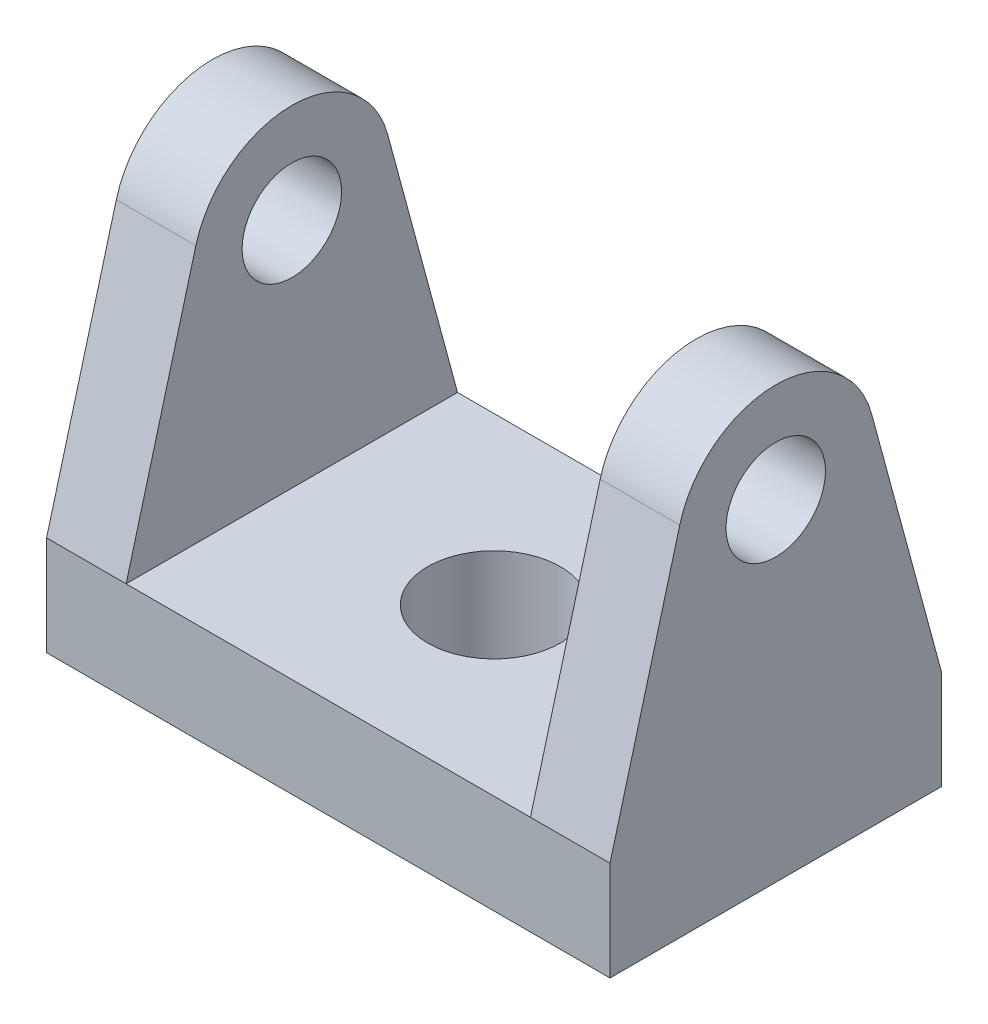
SolidWorks part; units mm, degrees
ref_plane "Front Plane" through (0, 0, 0) normal (0, 0, 1) x (1, 0, 0)
ref_plane "Top Plane" through (0, 0, 0) normal (0, 1, 0) x (1, 0, 0)
ref_plane "Right Plane" through (0, 0, 0) normal (1, 0, 0) x (0, 0, -1)
sketch "Sketch1" plane through (0, 0, 0) normal (0, 1, 0) x (1, 0, 0)
  line L1 (42.5, 25) -> (-42.5, 25)
  line L2 (42.5, 25) -> (42.5, -25)
  line L3 (42.5, -25) -> (-42.5, -25)
  line L4 (-42.5, 25) -> (-42.5, -25)
  line L5 (42.5, 25) -> (-42.5, -25) construction
  line L6 (42.5, -25) -> (-42.5, 25) construction
  circle A0 centre (0, 0) radius 10
  point P0 (0, 0)
  dimension "D3" = 20
  dimension "D1" = 85
  dimension "D2" = 50
extrude "Boss-Extrude1" add sketch "Sketch1" along normal blind 15
sketch "Sketch2" plane through (-42.5, 0, 0) normal (-1, 0, 0) x (0, 0, 1)
  line L0 (-25, 0) -> (25, 0) construction
  line L1 (-25, 15) -> (25, 15)
  line L2 (-25, 15) -> (-14.4802, 53.9145)
  line L3 (25, 15) -> (14.4802, 53.9145)
  circle A0 centre (0, 50) radius 7.5
  arc A1 (14.4802, 53.9145) -> (-14.4802, 53.9145) centre (0, 50) ccw
  dimension "D1" = 15
  dimension "D3" = 30
  dimension "D2" = 50
extrude "Boss-Extrude2" add sketch "Sketch2" against normal blind 12
mirror "Mirror1" about plane through (0, 0, 0) normal (1, 0, 0) of "Boss-Extrude2"
